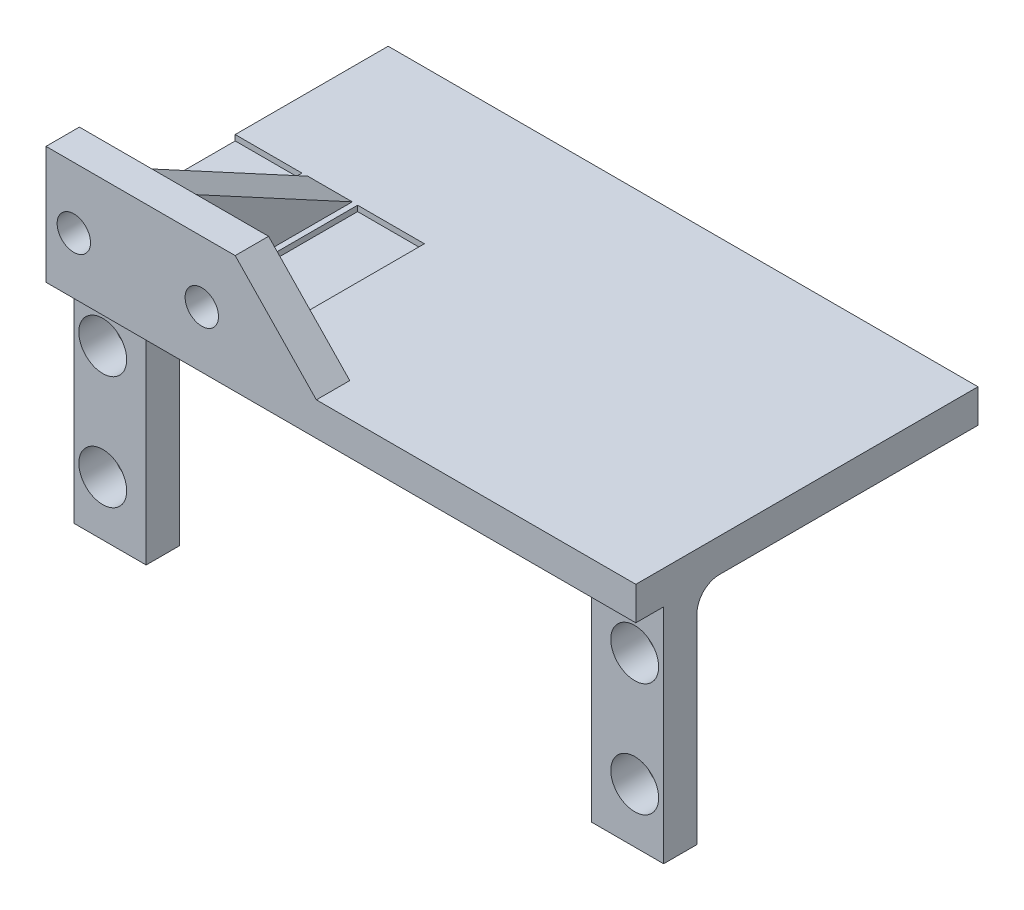
SolidWorks part; units mm, degrees
ref_plane "Front Plane" through (0, 0, 0) normal (0, 0, 1) x (1, 0, 0)
ref_plane "Top Plane" through (0, 0, 0) normal (0, 1, 0) x (1, 0, 0)
ref_plane "Right Plane" through (0, 0, 0) normal (1, 0, 0) x (0, 0, -1)
sketch "Sketch1" plane through (0, 0, 0) normal (0, 1, 0) x (1, 0, 0)
  line L1 (-2.3819, -6.7453) -> (50.6181, -6.7453)
  line L2 (-2.3819, -6.7453) -> (-2.3819, -37.4909)
  line L3 (-2.3819, -37.4909) -> (50.6181, -37.4909)
  line L4 (50.6181, -6.7453) -> (50.6181, -37.4909)
  dimension "D1" = 30.7456
  dimension "D2" = 53
extrude "Boss-Extrude1" add sketch "Sketch1" along normal blind 3
sketch "Sketch2" plane through (0, 0, 0) normal (0, -1, 0) x (1, 0, 0)
  line L1 (50.6181, 34.9909) -> (44.1181, 34.9909)
  line L2 (50.6181, 34.9909) -> (50.6181, 31.9909)
  line L3 (50.6181, 31.9909) -> (44.1181, 31.9909)
  line L4 (44.1181, 34.9909) -> (44.1181, 31.9909)
  line L6 (44.1181, 23.4909) -> (44.1181, 52.9909) construction
  line L7 (-2.3819, 6.7453) -> (-2.3819, 37.4909) construction
  line L8 (4.1181, 34.9909) -> (-2.3819, 34.9909)
  line L9 (4.1181, 34.9909) -> (4.1181, 31.9909)
  line L10 (4.1181, 31.9909) -> (-2.3819, 31.9909)
  line L11 (-2.3819, 34.9909) -> (-2.3819, 31.9909)
  line L14 (-2.3819, 37.4909) -> (50.6181, 37.4909) construction
  line L15 (50.6181, 6.7453) -> (-2.3819, 6.7453) construction
  dimension "D1" = 3
  dimension "D2" = 3
  dimension "D3" = 2.5
  dimension "D4" = 25.2456
  dimension "D5" = 6.5
  dimension "D6" = 2.5
  dimension "D7" = 3
  dimension "D8" = 6.5
  dimension "D9" = 6.5
extrude "Boss-Extrude2" add sketch "Sketch2" along normal blind 20
sketch "Sketch3" plane through (0, 0, 34.9909) normal (0, 0, 1) x (1, 0, 0)
  line L0 (-2.3819, -20) -> (-2.3819, 0) construction
  line L2 (-2.3819, 3) -> (50.6181, 3) construction
  line L3 (50.6181, -20) -> (50.6181, 0) construction
  circle A0 centre (48.0181, -15.1) radius 2.15
  circle A1 centre (48.0181, -4.9) radius 2.15
  circle A2 centre (0.2181, -15.1) radius 2.15
  circle A3 centre (0.2181, -4.9) radius 2.15
  dimension "D1" = 4.3
  dimension "D2" = 4.3
  dimension "D3" = 4.3
  dimension "D4" = 4.3
  dimension "D5" = 2.6
  dimension "D6" = 7.9
  dimension "D7" = 10.2
  dimension "D8" = 2.6
  dimension "D9" = 7.9
  dimension "D10" = 10.2
extrude "Cut-Extrude1" cut sketch "Sketch3" against normal blind 3
sketch "Sketch6" plane through (0, 0, 37.4909) normal (0, 0, 1) x (1, 0, 0)
  line L1 (-2.3819, 3) -> (14.6181, 3)
  line L2 (-2.3819, 3) -> (-2.3819, 10.58)
  line L3 (-2.3819, 10.58) -> (14.6181, 10.58)
  line L4 (14.6181, 3) -> (14.6181, 10.58)
  dimension "D1" = 17
  dimension "D2" = 7.58
extrude "Boss-Extrude3" add sketch "Sketch6" against normal blind 3
sketch "Sketch7" plane through (0, 0, 37.4909) normal (0, 0, 1) x (1, 0, 0)
  line L0 (14.6181, 3) -> (14.6181, 10.58) construction
  line L1 (14.6181, 10.58) -> (-2.3819, 10.58) construction
  circle A1 centre (0.1181, 5.0812) radius 1.5
  circle A3 centre (11.6181, 5.0812) radius 1.5
  dimension "D1" = 3
  dimension "D2" = 3
  dimension "D3" = 3
  dimension "D4" = 5.4988
  dimension "D5" = 11.5
extrude "Cut-Extrude2" cut sketch "Sketch7" against normal blind 7.5
sketch "Sketch8" plane through (0, 3, 0) normal (0, 1, 0) x (1, 0, 0)
  line L1 (-2.3819, -34.4909) -> (3.6181, -34.4909)
  line L2 (-2.3819, -34.4909) -> (-2.3819, -20.4909)
  line L3 (-2.3819, -20.4909) -> (3.6181, -20.4909)
  line L4 (3.6181, -34.4909) -> (3.6181, -20.4909)
  line L6 (-2.3819, -6.7453) -> (-2.3819, -34.4909)
  line L7 (-2.3819, -34.4909) -> (14.6181, -34.4909)
  line L8 (14.6181, -34.4909) -> (14.6181, -37.4909)
  line L9 (14.6181, -37.4909) -> (50.6181, -37.4909)
  line L10 (50.6181, -37.4909) -> (50.6181, -6.7453)
  line L11 (50.6181, -6.7453) -> (-2.3819, -6.7453)
  line L16 (50.6181, -37.4909) -> (50.6181, -6.7453)
  line L18 (14.6181, -34.4909) -> (8.6181, -34.4909)
  line L19 (14.6181, -34.4909) -> (14.6181, -20.4909)
  line L20 (14.6181, -20.4909) -> (8.6181, -20.4909)
  line L21 (8.6181, -34.4909) -> (8.6181, -20.4909)
  line L22 (14.6181, -37.4909) -> (50.6181, -37.4909) construction
  line M15 (-2.3819, -6.7453) -> (-2.3819, -34.4909)
  line M16 (-2.3819, -34.4909) -> (14.6181, -34.4909)
  dimension "D2" = 6
  dimension "D3" = 6
  dimension "D4" = 17
  dimension "D1" = 0
extrude "Cut-Extrude3" cut sketch "Sketch8" against normal blind 0.5 contours L21 L19 L20 M16 | L4 L3 M16 M15
fillet "Fillet1" radius 2 2 edges at (47.3681, 0, 31.9909) (0.8681, 0, 31.9909)
ref_plane "Plane1" through (6.1181, 0, 0) normal (-1, 0, 0) x (0, 0, 1)
sketch "Sketch13" plane through (6.1181, 0, 0) normal (-1, 0, 0) x (0, 0, 1)
  line L0 (34.4909, 10.5703) -> (34.4909, 3)
  line L1 (34.4909, 10.58) -> (34.4909, 2.5) construction
  line L2 (34.4909, 3) -> (20.4689, 3)
  line L4 (20.4689, 3) -> (34.4909, 10.5703)
  point P6 (20.4689, 3)
  point P8 (0, 0)
  point P9 (34.4909, 10.5703)
  point P10 (27.4909, 3)
  point P11 (0, 0)
extrude "Boss-Extrude4" add sketch "Sketch13" along normal blind 2 and the other way blind 2
sketch "Sketch14" plane through (0, 0, 37.4909) normal (0, 0, 1) x (1, 0, 0)
  line L0 (14.6181, 3) -> (14.6181, 10.58)
  line L1 (14.6181, 3) -> (21.9121, 3)
  line L2 (14.6181, 3) -> (50.6181, 3) construction
  line L3 (21.9121, 3) -> (14.6181, 10.58)
extrude "Boss-Extrude5" add sketch "Sketch14" against normal blind 3
